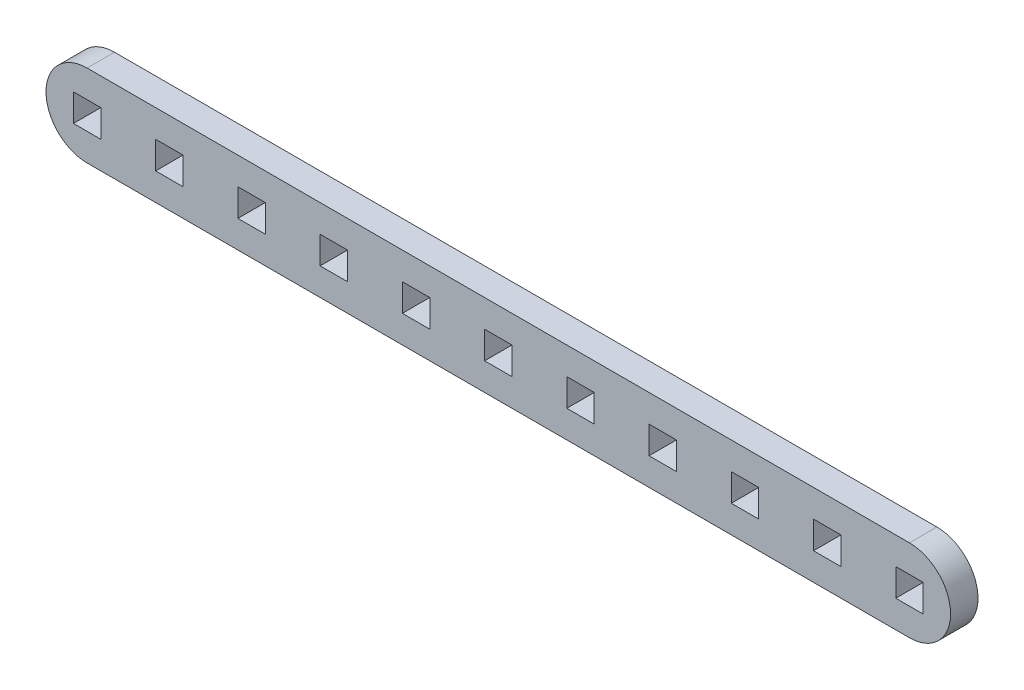
SolidWorks part; units mm, degrees
ref_plane "Alzado" through (0, 0, 0) normal (0, 0, 1) x (1, 0, 0)
ref_plane "Planta" through (0, 0, 0) normal (0, 1, 0) x (1, 0, 0)
ref_plane "Vista lateral" through (0, 0, 0) normal (1, 0, 0) x (0, 0, -1)
sketch "Model" plane through (0, 0, 0) normal (0, 0, 1) x (1, 0, 0)
  line L0 (8.4048, 293.775) -> (8.4048, 290.775)
  line L1 (11.4048, 293.775) -> (8.4048, 293.775)
  line L2 (11.4048, 290.775) -> (11.4048, 293.775)
  line L3 (8.4048, 290.775) -> (11.4048, 290.775)
  line L4 (17.4048, 293.775) -> (17.4048, 290.775)
  line L5 (20.4048, 293.775) -> (17.4048, 293.775)
  line L6 (20.4048, 290.775) -> (20.4048, 293.775)
  line L7 (17.4048, 290.775) -> (20.4048, 290.775)
  line L8 (26.4048, 293.775) -> (26.4048, 290.775)
  line L9 (29.4048, 293.775) -> (26.4048, 293.775)
  line L10 (29.4048, 290.775) -> (29.4048, 293.775)
  line L11 (26.4048, 290.775) -> (29.4048, 290.775)
  line L12 (35.4048, 293.775) -> (35.4048, 290.775)
  line L13 (38.4048, 293.775) -> (35.4048, 293.775)
  line L14 (38.4048, 290.775) -> (38.4048, 293.775)
  line L15 (35.4048, 290.775) -> (38.4048, 290.775)
  line L16 (44.4048, 293.775) -> (44.4048, 290.775)
  line L17 (47.4048, 293.775) -> (44.4048, 293.775)
  line L18 (47.4048, 290.775) -> (47.4048, 293.775)
  line L19 (44.4048, 290.775) -> (47.4048, 290.775)
  line L20 (53.4048, 293.775) -> (53.4048, 290.775)
  line L21 (56.4048, 293.775) -> (53.4048, 293.775)
  line L22 (56.4048, 290.775) -> (56.4048, 293.775)
  line L23 (53.4048, 290.775) -> (56.4048, 290.775)
  line L24 (62.4048, 293.775) -> (62.4048, 290.775)
  line L25 (65.4048, 293.775) -> (62.4048, 293.775)
  line L26 (65.4048, 290.775) -> (65.4048, 293.775)
  line L27 (62.4048, 290.775) -> (65.4048, 290.775)
  line L28 (71.4048, 293.775) -> (71.4048, 290.775)
  line L29 (74.4048, 293.775) -> (71.4048, 293.775)
  line L30 (74.4048, 290.775) -> (74.4048, 293.775)
  line L31 (71.4048, 290.775) -> (74.4048, 290.775)
  line L32 (80.4048, 293.775) -> (80.4048, 290.775)
  line L33 (83.4048, 293.775) -> (80.4048, 293.775)
  line L34 (83.4048, 290.775) -> (83.4048, 293.775)
  line L35 (80.4048, 290.775) -> (83.4048, 290.775)
  line L36 (89.4048, 293.775) -> (89.4048, 290.775)
  line L37 (92.4048, 293.775) -> (89.4048, 293.775)
  line L38 (92.4048, 290.775) -> (92.4048, 293.775)
  line L39 (89.4048, 290.775) -> (92.4048, 290.775)
  line L40 (98.4048, 293.775) -> (98.4048, 290.775)
  line L41 (101.4048, 293.775) -> (98.4048, 293.775)
  line L42 (101.4048, 290.775) -> (101.4048, 293.775)
  line L43 (98.4048, 290.775) -> (101.4048, 290.775)
  line L44 (9.9048, 296.775) -> (99.9048, 296.775)
  line L45 (9.9048, 287.775) -> (99.9048, 287.775)
  arc A0 (9.9048, 296.775) -> (9.9048, 287.775) centre (9.9048, 292.275) ccw
  arc A1 (99.9048, 287.775) -> (99.9048, 296.775) centre (99.9048, 292.275) ccw
extrude "Saliente-Extruir1" add sketch "Model" along normal blind 3
